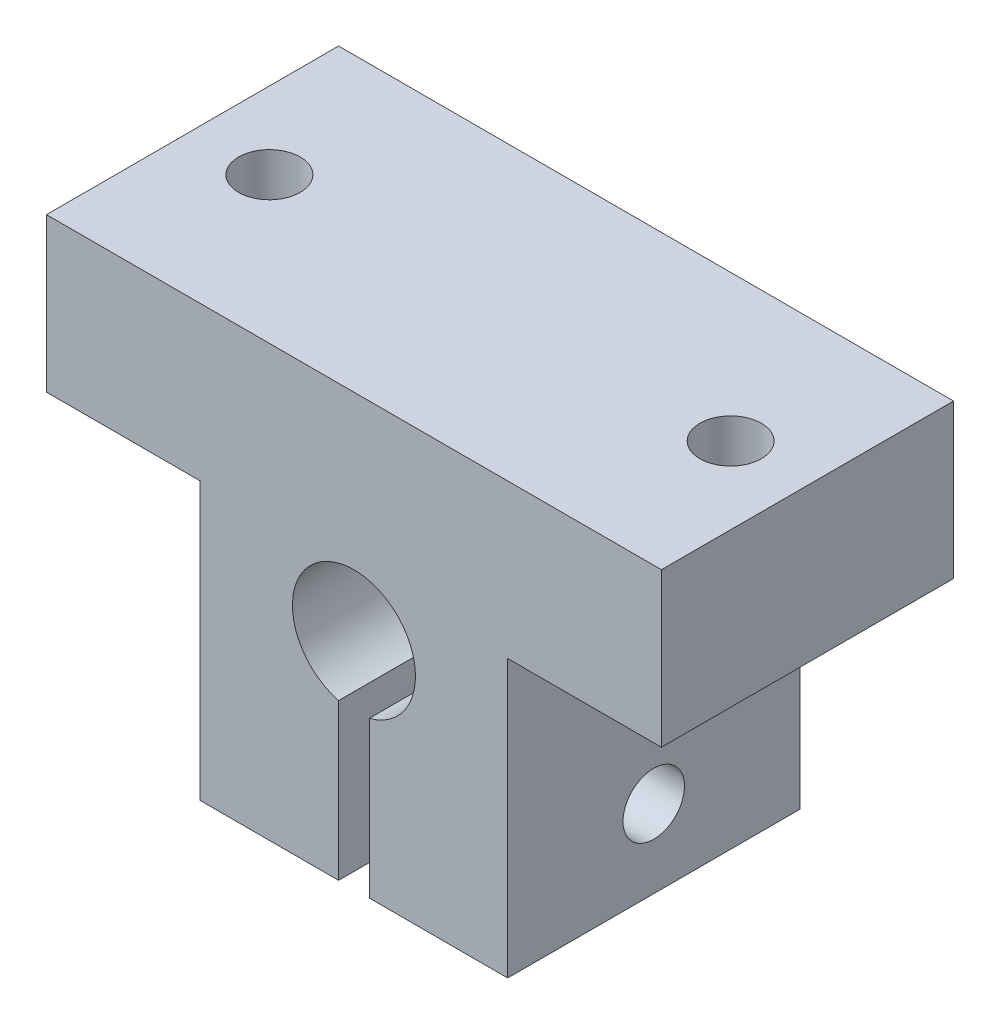
SolidWorks part; units mm, degrees
ref_plane "Front Plane" through (0, 0, 0) normal (0, 0, 1) x (1, 0, 0)
ref_plane "Top Plane" through (0, 0, 0) normal (0, 1, 0) x (1, 0, 0)
ref_plane "Right Plane" through (0, 0, 0) normal (1, 0, 0) x (0, 0, -1)
sketch "Sketch1" plane through (0, 0, 0) normal (0, 0, 1) x (1, 0, 0)
  line L0 (50, 0) -> (90, 0)
  line L1 (90, 0) -> (90, -10)
  line L3 (90, -10) -> (80, -10)
  line L4 (80, -10) -> (80, -28)
  line L5 (80, -28) -> (60, -28)
  line L6 (60, -28) -> (60, -10)
  line L7 (60, -10) -> (50, -10)
  line L8 (50, 0) -> (50, -10)
  line L9 (70, -28) -> (70, 0) construction
  circle A3 centre (70, -14) radius 4
  point P8 (90.6748, 0)
  point P10 (70, 0)
  point P11 (0, 0)
  point P12 (90, 0)
  dimension "D3" = 8
  dimension "D4" = 10
  dimension "D5" = 10
  dimension "D1" = 20
  dimension "D2" = 10
  dimension "D6" = 10
extrude "Boss-Extrude1" add sketch "Sketch1" along normal blind 19
sketch "Sketch3" plane through (0, -10, 0) normal (0, -1, 0) x (-1, 0, 0)
  line L0 (-60, -19) -> (-50, 0) construction
  line L1 (-80, -19) -> (-90, 0) construction
  line L2 (-80, -19) -> (-90, -19) construction
  line L3 (-80, -19) -> (-80, 0) construction
  circle A0 centre (-85, -9.5) radius 2
  circle A1 centre (-55, -9.5) radius 2
  dimension "D1" = 4
  dimension "D2" = 4
extrude "Cut-Extrude2" cut sketch "Sketch3" against normal up to surface (10 mm away) up to face at (70, 0, 9.5)
sketch "Sketch4" plane through (0, 0, 19) normal (0, 0, 1) x (1, 0, 0)
  line L0 (60, -28) -> (80, -28) construction
  line L1 (71, -40.7761) -> (69, -40.7761)
  line L2 (71, -40.7761) -> (71, -15.2239)
  line L3 (71, -15.2239) -> (69, -15.2239)
  line L4 (69, -40.7761) -> (69, -15.2239)
  line L5 (71, -40.7761) -> (69, -15.2239) construction
  line L6 (71, -15.2239) -> (69, -40.7761) construction
  point P0 (70, -28)
  dimension "D1" = 2
extrude "Cut-Extrude3" cut sketch "Sketch4" against normal up to surface (19 mm away) up to face at (70, -12, 0)
sketch "Sketch5" plane through (71, 0, 0) normal (-1, 0, 0) x (0, 0, 1)
  line L0 (19, -17.873) -> (0, -28) construction
  circle A0 centre (9.5, -22.9365) radius 2
  point P6 (0, 0)
  dimension "D1" = 4
extrude "Cut-Extrude4" cut sketch "Sketch5" against normal through all and the other way through all
